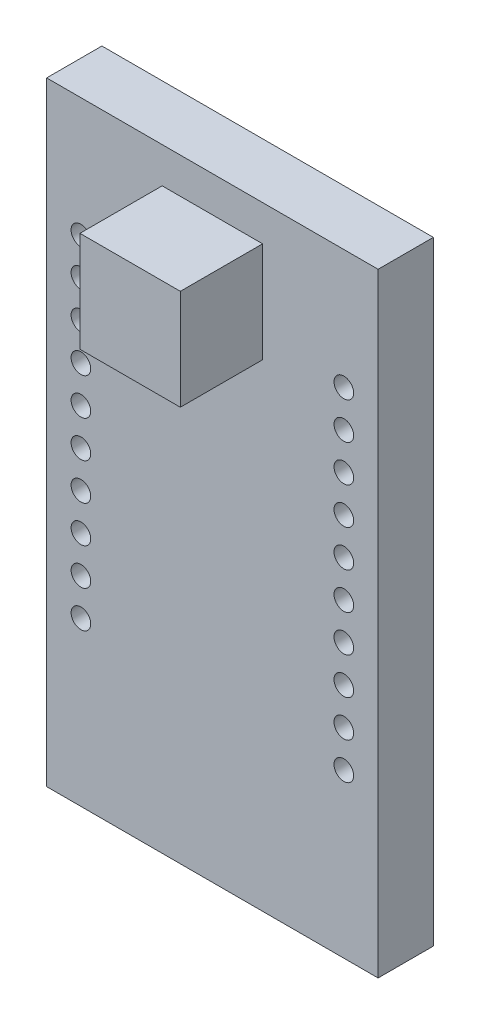
SolidWorks part; units mm, degrees
ref_plane "Front Plane" through (0, 0, 0) normal (0, 0, 1) x (1, 0, 0)
ref_plane "Top Plane" through (0, 0, 0) normal (0, 1, 0) x (1, 0, 0)
ref_plane "Right Plane" through (0, 0, 0) normal (1, 0, 0) x (0, 0, -1)
sketch "Sketch1" plane through (0, 0, 0) normal (0, 0, 1) x (1, 0, 0)
  line L1 (-13.5, 25) -> (13.5, 25)
  line L2 (-13.5, 25) -> (-13.5, -25)
  line L3 (-13.5, -25) -> (13.5, -25)
  line L4 (13.5, 25) -> (13.5, -25)
  line L5 (-13.5, 25) -> (13.5, -25) construction
  line L6 (-13.5, -25) -> (13.5, 25) construction
  point P0 (0, 0)
  dimension "D1" = 27
  dimension "D2" = 50
extrude "Boss-Extrude1" add sketch "Sketch1" along normal blind 4.5
sketch "Sketch2" plane through (0, 0, 4.5) normal (0, 0, 1) x (1, 0, 0)
  line L1 (-4.09, 22.09) -> (4.09, 22.09)
  line L2 (-4.09, 22.09) -> (-4.09, 13.91)
  line L3 (-4.09, 13.91) -> (4.09, 13.91)
  line L4 (4.09, 22.09) -> (4.09, 13.91)
  line L5 (-4.09, 22.09) -> (4.09, 13.91) construction
  line L6 (-4.09, 13.91) -> (4.09, 22.09) construction
  point P0 (0, 18)
  point P5 (0, 0)
  dimension "D1" = 8.18
  dimension "D2" = 8.18
  dimension "D3" = 18
extrude "Boss-Extrude2" add sketch "Sketch2" along normal blind 6.7
sketch "Sketch3" plane through (0, 0, 4.5) normal (0, 0, 1) x (1, 0, 0)
  circle A0 centre (10.7093, 15.2711) radius 0.8
  circle A1 centre (10.7093, 12.2711) radius 0.8
  circle A2 centre (10.7093, 9.2711) radius 0.8
  circle A3 centre (10.7093, 6.2711) radius 0.8
  circle A4 centre (10.7093, 3.2711) radius 0.8
  circle A5 centre (10.7093, 0.2711) radius 0.8
  circle A6 centre (10.7093, -2.7289) radius 0.8
  circle A7 centre (10.7093, -5.7289) radius 0.8
  circle A8 centre (10.7093, -8.7289) radius 0.8
  circle A9 centre (10.7093, -11.7289) radius 0.8
  point P5 (10.7093, -16.2289)
  point P13 (10.7093, -22.2289)
  point P18 (10.7093, -28.2289)
  point P23 (10.7093, -34.2289)
  point P28 (10.7093, -40.2289)
  dimension "D1" = 1.6
  dimension "D2" = 1.6
  dimension "D3" = 3
  dimension "D4" = 5
extrude "Cut-Extrude1" cut sketch "Sketch3" against normal blind 6.7
mirror "Mirror1" about plane through (0, 0, 0) normal (1, 0, 0) of "Cut-Extrude1"
